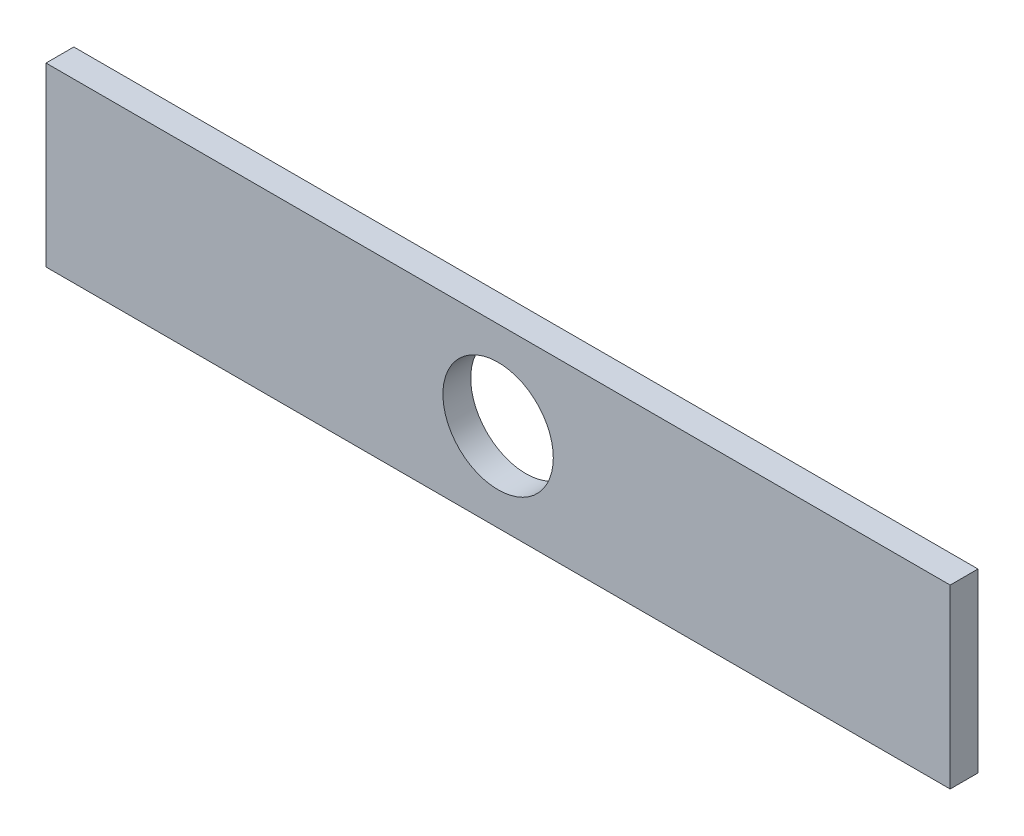
SolidWorks part; units mm, degrees
ref_plane "Alzado" through (0, 0, 0) normal (0, 0, 1) x (1, 0, 0)
ref_plane "Planta" through (0, 0, 0) normal (0, 1, 0) x (1, 0, 0)
ref_plane "Vista lateral" through (0, 0, 0) normal (1, 0, 0) x (0, 0, -1)
sketch "Croquis1" plane through (0, 0, 0) normal (0, 0, 1) x (1, 0, 0)
  line L1 (65, -12.7) -> (-65, -12.7)
  line L2 (65, -12.7) -> (65, 12.7)
  line L3 (65, 12.7) -> (-65, 12.7)
  line L4 (-65, -12.7) -> (-65, 12.7)
  line L5 (65, -12.7) -> (-65, 12.7) construction
  line L6 (65, 12.7) -> (-65, -12.7) construction
  circle A0 centre (0, 0) radius 7.9375
  point P0 (0, 0)
  dimension "D3" = 15.875
  dimension "D1" = 130
  dimension "D2" = 25.4
extrude "Saliente-Extruir1" add sketch "Croquis1" along normal blind 4
